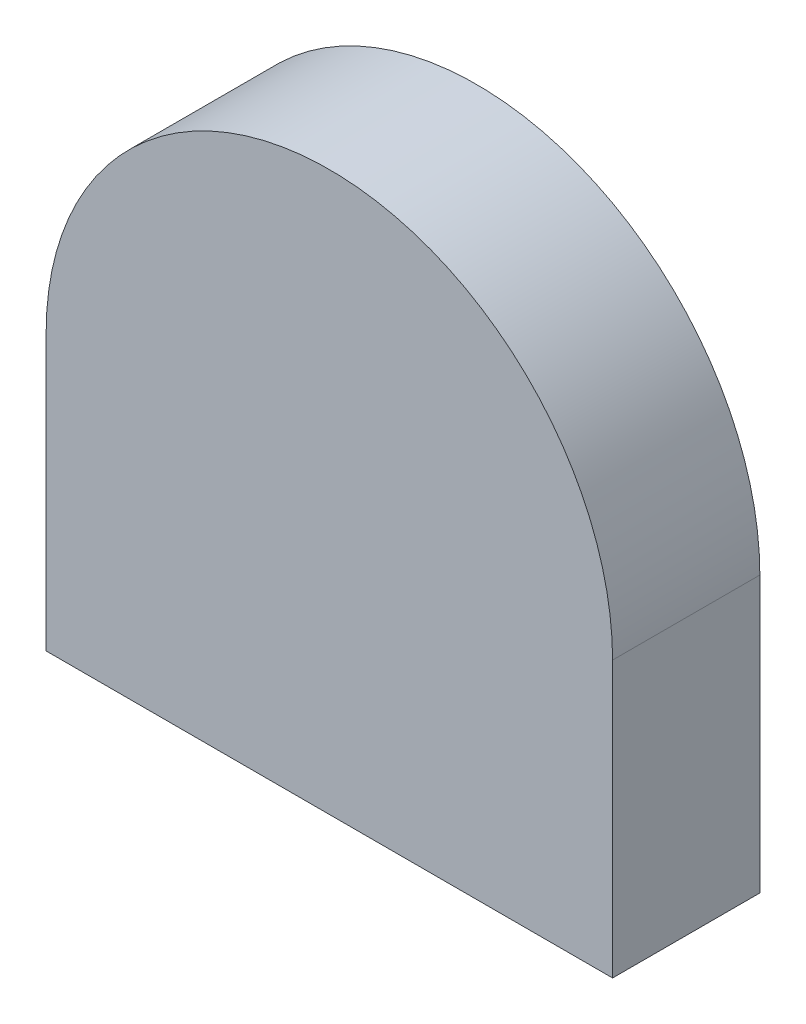
SolidWorks part; units mm, degrees
ref_plane "Plan de face" through (0, 0, 0) normal (0, 0, 1) x (1, 0, 0)
ref_plane "Plan de dessus" through (0, 0, 0) normal (0, 1, 0) x (1, 0, 0)
ref_plane "Plan de droite" through (0, 0, 0) normal (1, 0, 0) x (0, 0, -1)
sketch "Esquisse1" plane through (0, 0, 0) normal (0, 0, 1) x (1, 0, 0)
  line L0 (-25, 0) -> (-25, -32.4754)
  line L1 (-25, -32.4754) -> (25, -32.4754)
  line L2 (25, 0) -> (25, -32.4754)
  circle A0 centre (0, 0) radius 14
  arc A2 (-25, 0) -> (25, 0) centre (0, 0) cw
extrude "Boss.-Extru.1" add sketch "Esquisse1" along normal blind 13 contours A2 L0 L1 L2 A0
sketch "Esquisse3" plane through (0, 0, 13) normal (0, 0, 1) x (1, 0, 0)
  circle A0 centre (0, 0) radius 14
extrude "Boss.-Extru.2" add sketch "Esquisse3" against normal blind 2
sketch "Esquisse4" plane through (-25, 0, 0) normal (-1, 0, 0) x (0, 0, 1)
  line L2 (0, -24.3054) -> (13, -24.3054)
  line L3 (0, 0) -> (0, -32.4754) construction
  line L4 (13, 0) -> (13, -32.4754) construction
  line L5 (13, -24.3054) -> (13, -34.3213)
  line L6 (13, -34.3213) -> (0, -34.3213)
  line L7 (0, -34.3213) -> (0, -24.3054)
extrude "Enlèv. mat.-Extru.1" cut sketch "Esquisse4" against normal blind 60
